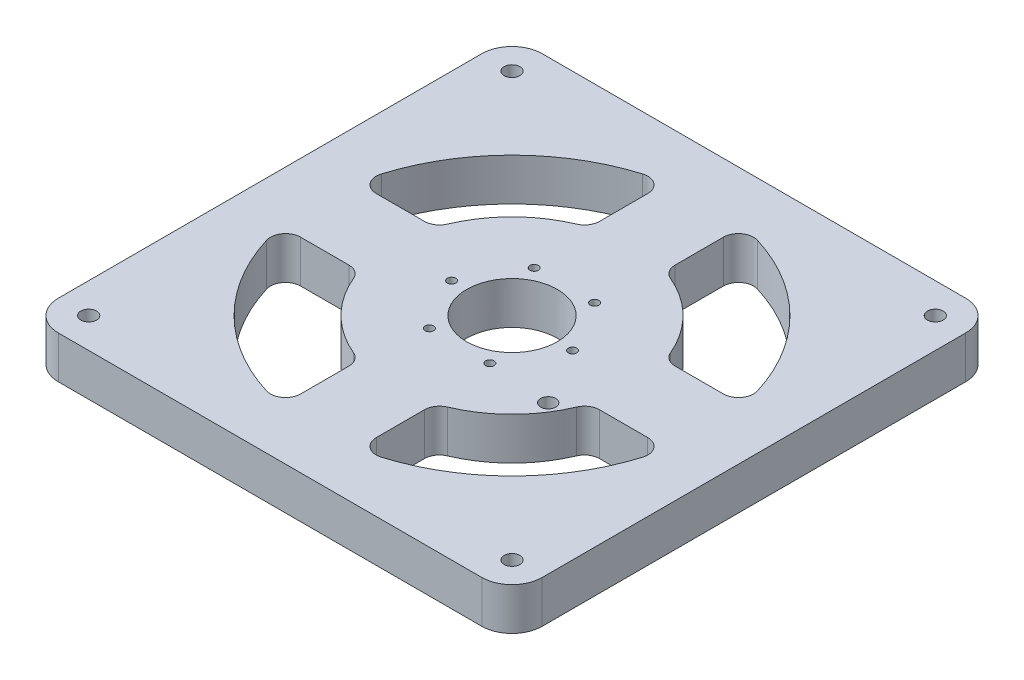
SolidWorks part; units mm, degrees
ref_plane "前视基准面" through (0, 0, 0) normal (0, 0, 1) x (1, 0, 0)
ref_plane "上视基准面" through (0, 0, 0) normal (0, 1, 0) x (1, 0, 0)
ref_plane "右视基准面" through (0, 0, 0) normal (1, 0, 0) x (0, 0, -1)
other "Configuration Table"
sketch "草图1" plane through (0, 0, 0) normal (0, 1, 0) x (1, 0, 0)
  line L1 (0, 0) -> (160, 0)
  line L2 (0, 0) -> (0, 160)
  line L3 (0, 160) -> (160, 160)
  line L4 (160, 0) -> (160, 160)
  dimension "D1" = 160
  dimension "D2" = 160
extrude "凸台-拉伸1" add sketch "草图1" along normal blind 14
sketch "草图2" plane through (0, 14, 0) normal (0, 1, 0) x (1, 0, 0)
  line L0 (80, 200) -> (80, -49800) construction
  line L1 (160, 160) -> (0, 160) construction
  line L2 (200, 80) -> (-49800, 80) construction
  line L3 (160, 0) -> (160, 160) construction
  circle A0 centre (80, 80) radius 15
  circle A1 centre (80, 80) radius 20 construction
  circle A2 centre (60, 80) radius 1.4
  circle A3 centre (70, 97.3205) radius 1.4
  circle A4 centre (90, 97.3205) radius 1.4
  circle A5 centre (100, 80) radius 1.4
  circle A6 centre (90, 62.6795) radius 1.4
  circle A7 centre (70, 62.6795) radius 1.4
  point P6 (80, 160)
  point P11 (160, 80)
  point P27 (80, 80)
  dimension "D1" = 30
  dimension "D2" = 40
  dimension "D3" = 2.8
  dimension "D4" = 6
extrude "切除-拉伸1" cut sketch "草图2" against normal blind 16
sketch "草图3" plane through (0, 14, 0) normal (0, 1, 0) x (1, 0, 0)
  line L0 (160, 160) -> (0, 160) construction
  line L1 (0, 160) -> (0, 0) construction
  line L2 (80, 200) -> (80, -49800) construction
  line L3 (200, 80) -> (50200, 80) construction
  line L4 (160, 0) -> (160, 160) construction
  circle A0 centre (10, 150) radius 2.6
  circle A1 centre (150, 150) radius 2.6
  circle A2 centre (150, 10) radius 2.6
  circle A3 centre (10, 10) radius 2.6
  point P9 (80, 160)
  point P13 (160, 80)
  dimension "D1" = 5.2
  dimension "D2" = 10
  dimension "D3" = 10
extrude "切除-拉伸2" cut sketch "草图3" against normal blind 20
fillet "圆角1" radius 10 4 edges at (0, 7, -160) (160, 7, -160) (160, 7, 0) (0, 7, 0)
sketch "草图5" plane through (0, 0, 0) normal (0, -1, 0) x (1, 0, 0)
  circle A0 centre (80, -80) radius 20 construction
  circle A1 centre (100, -80) radius 3.5
  circle A2 centre (90, -97.3205) radius 3.5
  circle A3 centre (70, -97.3205) radius 3.5
  circle A4 centre (60, -80) radius 3.5
  circle A5 centre (70, -62.6795) radius 3.5
  circle A6 centre (90, -62.6795) radius 3.5
  point P19 (80, -80)
  dimension "D1" = 7
  dimension "D2" = 6
extrude "切除-拉伸3" cut sketch "草图5" against normal blind 4
sketch "草图6" plane through (0, 14, 0) normal (0, 1, 0) x (1, 0, 0)
  line L0 (80, 80) -> (50080, 80) construction
  line L1 (80, 80) -> (80, 50080) construction
  line L2 (16.2132, 92.5) -> (42.0033, 92.5)
  line L3 (16.2132, 67.5) -> (42.0033, 67.5)
  line L4 (143.7868, 92.5) -> (117.9967, 92.5)
  line L5 (143.7868, 67.5) -> (117.9967, 67.5)
  line L6 (81.3711, 81.3711) -> (35436.7101, 35436.7101) construction
  line L7 (92.5, 143.7868) -> (92.5, 117.9967)
  line L8 (67.5, 143.7868) -> (67.5, 117.9967)
  line L9 (92.5, 16.2132) -> (92.5, 42.0033)
  line L10 (67.5, 16.2132) -> (67.5, 42.0033)
  circle A0 centre (80, 80) radius 40
  circle A1 centre (80, 80) radius 65
  dimension "D1" = 130
  dimension "D2" = 80
  dimension "D3" = 25
extrude "切除-拉伸4" cut sketch "草图6" against normal blind 20 contours L8 A1 L2 A0 | L4 A1 L7 A0 | L9 A1 L5 A0 | L3 A1 L10 A0
sketch "草图7" plane through (0, 14, 0) normal (0, 1, 0) x (1, 0, 0)
  circle A1 centre (110.9732, 60.9933) radius 2.5
  dimension "D2" = 5
extrude "切除-拉伸5" cut sketch "草图7" against normal blind 20
fillet "圆角2" radius 5 4 edges at (42.0033, 7, -92.5) (16.2132, 7, -92.5) (67.5, 7, -117.9967) (67.5, 7, -143.7868)
fillet "圆角3" radius 5 12 edges at (92.5, 7, -16.2132) (143.7868, 7, -92.5) (67.5, 7, -16.2132) (117.9967, 7, -92.5) (143.7868, 7, -67.5) (67.5, 7, -42.0033) (42.0033, 7, -67.5) (16.2132, 7, -67.5) (92.5, 7, -42.0033) (117.9967, 7, -67.5) (92.5, 7, -143.7868) (92.5, 7, -117.9967)
